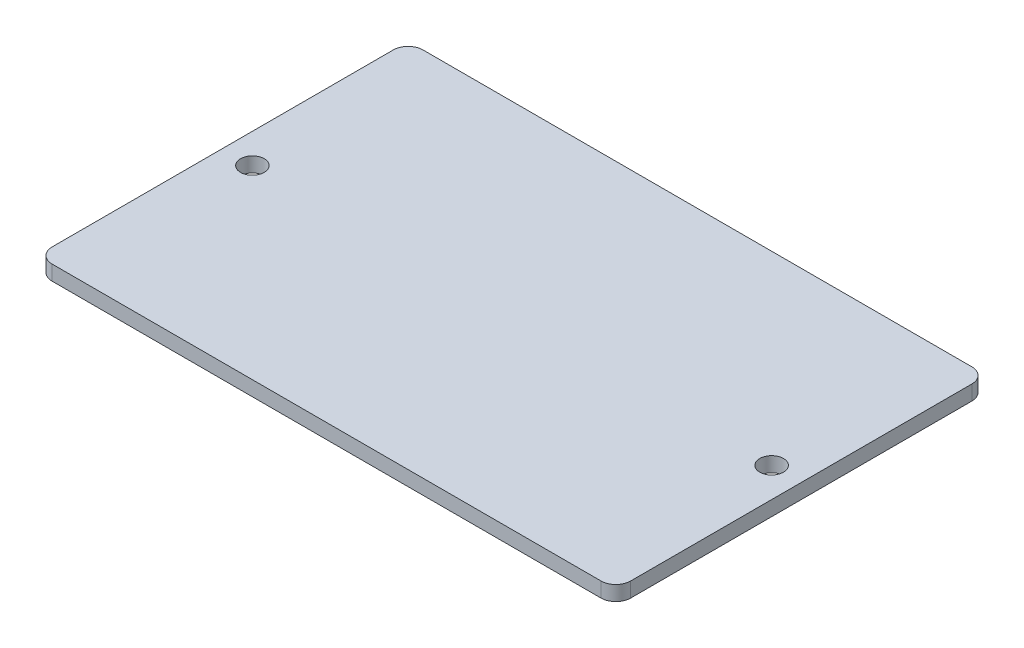
SolidWorks part; units mm, degrees
material "ABS"
ref_plane "前视基准面" through (0, 0, 0) normal (0, 0, 1) x (1, 0, 0)
ref_plane "上视基准面" through (0, 0, 0) normal (0, 1, 0) x (1, 0, 0)
ref_plane "右视基准面" through (0, 0, 0) normal (1, 0, 0) x (0, 0, -1)
sketch "草图1" plane through (0, 0, 0) normal (0, 1, 0) x (1, 0, 0)
  line L0 (-39, 0) -> (39, 0) construction
  line L1 (-37, -25) -> (37, -25)
  line L2 (-39, -23) -> (-39, 23)
  line L3 (-37, 25) -> (37, 25)
  line L4 (39, -23) -> (39, 23)
  line L5 (-39, -25) -> (39, 25) construction
  line L6 (-39, 25) -> (39, -25) construction
  line L7 (0, -55) -> (0, 55) construction
  arc A0 (-39, -23) -> (-37, -25) centre (-37, -23) ccw
  arc A1 (37, -25) -> (39, -23) centre (37, -23) ccw
  arc A2 (39, 23) -> (37, 25) centre (37, 23) ccw
  arc A3 (-39, 23) -> (-37, 25) centre (-37, 23) cw
  circle A4 centre (-35, 0) radius 1.6
  circle A5 centre (35, 0) radius 1.6
  point P0 (0, 0)
  point P21 (0, 0)
  dimension "D3" = 2
  dimension "D4" = 3.2
  dimension "D5" = 4
  dimension "D1" = 78
  dimension "D2" = 50
extrude "凸台-拉伸1" add sketch "草图1" along normal blind 2
sketch "草图2" plane through (0, 2, 0) normal (0, 1, 0) x (1, 0, 0)
  line L0 (-3.5993, 4.5991) -> (0.6131, 7.7585)
  line L1 (-12.9154, -2.3688) -> (-8.2163, 1.1557)
  spline S0 degree 3 poles (26.2814, -1.3089) (28.1154, -0.265) (29.9495, 0.7789) (31.7835, 1.8227) knots 14 14 14 14 15 15 15 15
  spline S1 degree 3 poles (31.7835, 1.8227) (29.2173, 2.7128) (26.3386, 3.7554) (23.2029, 4.9651) knots 15 15 15 15 16 16 16 16
  spline S2 degree 3 poles (23.2029, 4.9651) (20.0402, 6.1853) (18.4256, 6.8774) (17.03, 8.5408) knots 0 0 0 0 1 1 1 1
  spline S3 degree 3 poles (17.03, 8.5408) (15.8454, 9.9528) (15.3173, 11.4702) (15.0593, 12.5263) knots 1 1 1 1 2 2 2 2
  spline S4 degree 3 poles (15.0593, 12.5263) (12.6785, 13.0737) (9.1023, 13.9003) (4.7376, 14.9271) knots 2 2 2 2 3 3 3 3
  spline S5 degree 3 poles (4.7376, 14.9271) (-2.022, 16.5173) (-2.8061, 16.7369) (-4.7263, 17.0974) knots 3 3 3 3 4 4 4 4
  spline S6 degree 3 poles (-4.7263, 17.0974) (-13.2281, 18.6937) (-19.1333, 18.3843) (-19.1356, 18.3427) knots 4 4 4 4 5 5 5 5
  spline S7 degree 3 poles (-19.1356, 18.3427) (-19.1382, 18.2953) (-11.4761, 18.5805) (-2.8406, 15.1406) knots 5 5 5 5 6 6 6 6
  spline S8 degree 3 poles (-2.8406, 15.1406) (-0.1429, 14.066) (4.15, 12.309) (4.1328, 10.0173) knots 6 6 6 6 7 7 7 7
  spline S9 degree 3 poles (4.1328, 10.0173) (4.1241, 8.8638) (2.1456, 7.3266) (-1.8115, 4.2522) knots 7 7 7 7 8 8 8 8
  spline S10 degree 3 poles (-1.8115, 4.2522) (-2.7261, 3.5416) (-3.1939, 3.2154) (-5.5742, 1.43) knots 8 8 8 8 9 9 9 9
  spline S11 degree 3 poles (-5.5742, 1.43) (-5.632, 1.3866) (-10.2707, -2.0925) (-10.2733, -2.0945) (-12.4656, -3.7388) (-18.1649, -8.0284) (-32.9223, -19.1571) knots 9 9 9 9 10 10 10 11 11 11 11
  spline S12 degree 3 poles (-32.9223, -19.1571) (-25.4339, -14.6943) (-17.6328, -10.7316) (-10.0282, -7.9926) (1.3678, -3.8882) (13.6678, -1.2255) (13.6678, -1.2255) knots 11.755593 11.755593 11.755593 11.755593 12 12 12 13 13 13 13
  spline S13 degree 3 poles (13.6678, -1.2255) (18.5756, -0.9114) (22.855, -1.0438) (26.2814, -1.3089) knots 13 13 13 13 14 14 14 14
  spline S14 degree 3 poles (-10.1342, 6.2727) (-7.7149, 5.8123) (-5.5293, 5.2243) (-3.5993, 4.5991) knots 1 1 1 1 2 2 2 2
  spline S15 degree 3 poles (0.6131, 7.7585) (-2.3884, 8.0252) (-5.7408, 8.1707) (-9.3871, 8.0872) knots 4 4 4 4 5 5 5 5
  spline S16 degree 3 poles (-9.3871, 8.0872) (-13.2611, 7.9984) (-16.7963, 7.6665) (-19.9314, 7.2221) knots 3 3 3 3 4 4 4 4
  spline S17 degree 3 poles (-19.9314, 7.2221) (-17.1205, 7.2067) (-13.8011, 6.9704) (-10.1342, 6.2727) knots 2 2 2 2 3 3 3 3
  spline S18 degree 3 poles (-17.3211, -2.453) (-15.773, -2.3618) (-14.3011, -2.3403) (-12.9154, -2.3688) knots 1 1 1 1 2 2 2 2
  spline S19 degree 3 poles (-8.2163, 1.1557) (-11.1236, 0.5536) (-14.1848, -0.1717) (-17.3745, -1.0476) knots 4 4 4 4 5 5 5 5
  spline S20 degree 3 poles (-17.3745, -1.0476) (-20.2838, -1.8466) (-23.0359, -2.6982) (-25.6243, -3.5746) knots 3 3 3 3 4 4 4 4
  spline S21 degree 3 poles (-25.6243, -3.5746) (-23.1846, -3.056) (-20.4004, -2.6343) (-17.3211, -2.453) knots 2 2 2 2 3 3 3 3
